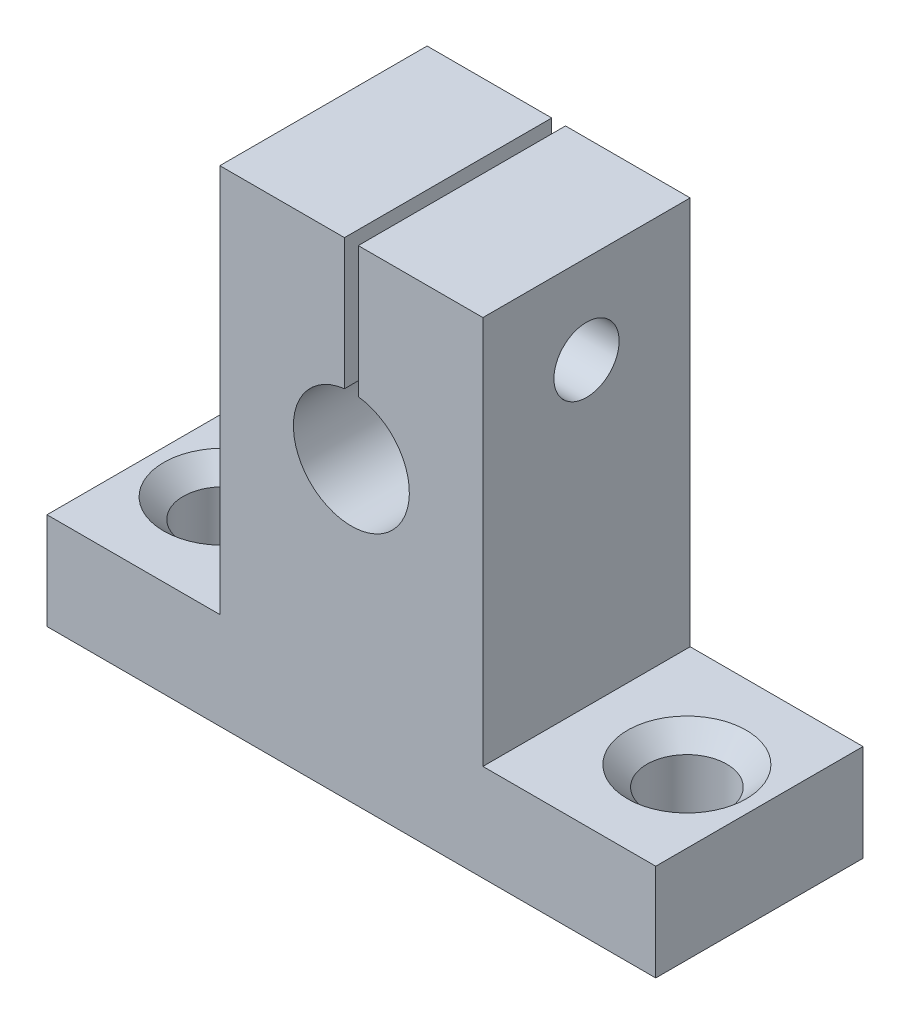
SolidWorks part; units mm, degrees
ref_plane "Front Plane" through (0, 0, 0) normal (0, 0, 1) x (1, 0, 0)
ref_plane "Top Plane" through (0, 0, 0) normal (0, 1, 0) x (1, 0, 0)
ref_plane "Right Plane" through (0, 0, 0) normal (1, 0, 0) x (0, 0, -1)
sketch "Sketch1" plane through (0, 0, 0) normal (0, 0, 1) x (1, 0, 0)
  line L1 (0, 0) -> (42, 0)
  line L2 (0, 0) -> (0, 6.68)
  line L3 (0, 6.68) -> (42, 6.68)
  line L4 (42, 0) -> (42, 6.68)
  line L5 (11.925, 6.68) -> (30.075, 6.68)
  line L6 (11.925, 6.68) -> (11.925, 33.5)
  line L7 (11.925, 33.5) -> (30.075, 33.5)
  line L8 (30.075, 6.68) -> (30.075, 33.5)
  line L9 (20.525, 33.5) -> (21.475, 33.5)
  line L10 (20.525, 33.5) -> (20.525, 20.5)
  line L11 (20.525, 20.5) -> (21.475, 20.5)
  line L12 (21.475, 33.5) -> (21.475, 20.5)
  circle A0 centre (21, 20.5) radius 4
  point P8 (21, 33.5)
  point P9 (21, 6.68)
  point P12 (21, 24.5)
  point P15 (21, 20.5)
  point P20 (21, 20.5)
  dimension "D5" = 8
  dimension "D1" = 18.15
  dimension "D2" = 6.68
  dimension "D3" = 42
  dimension "D4" = 33.5
  dimension "D6" = 0.95
  dimension "D7" = 9
sketch "Sketch2" plane through (0, 0, 0) normal (0, 0, 1) x (1, 0, 0)
  line L0 (11.925, 6.68) -> (0, 6.68)
  line L1 (20.525, 33.5) -> (11.925, 33.5)
  line L4 (11.925, 6.68) -> (30.075, 6.68)
  line L5 (30.075, 6.68) -> (30.075, 33.5)
  line L6 (30.075, 33.5) -> (11.925, 33.5)
  line L7 (11.925, 33.5) -> (11.925, 6.68)
  line L9 (30.075, 6.68) -> (30.075, 33.5)
  line L10 (30.075, 33.5) -> (21.475, 33.5)
  line L11 (11.925, 33.5) -> (11.925, 6.68)
  line L12 (0, 0) -> (42, 0)
  line L13 (42, 0) -> (42, 6.68)
  line L14 (42, 6.68) -> (0, 6.68)
  line L15 (0, 6.68) -> (0, 0)
  line L16 (0, 0) -> (42, 0)
  line L17 (42, 0) -> (42, 6.68)
  line L18 (42, 6.68) -> (30.075, 6.68)
  line L19 (0, 6.68) -> (0, 0)
  line L20 (21.475, 33.5) -> (20.525, 33.5)
  line L21 (20.525, 33.5) -> (20.525, 20.5)
  line L22 (20.525, 20.5) -> (21.475, 20.5)
  line L23 (21.475, 20.5) -> (21.475, 33.5)
  line L25 (20.525, 33.5) -> (20.525, 24.4717)
  line L27 (21.475, 24.4717) -> (21.475, 33.5)
  circle A1 centre (21, 20.5) radius 4
  arc A2 (20.525, 24.4717) -> (21.475, 24.4717) centre (21, 20.5) ccw
  dimension "D1" = 0
  dimension "D2" = 0
  dimension "D3" = 0
  dimension "D4" = 0
extrude "Boss-Extrude1" add sketch "Sketch2" along normal mid plane 14.3
hole_wizard "CBORE for M4 Hex Socket Head Cap Screw1" positions "Sketch3" profile "Sketch5" counterbore size "M4" standard "ISO" end condition through all
sketch "Sketch3" plane through (11.925, 0, 0) normal (-1, 0, 0) x (0, 0, 1)
  line L0 (7.15, 33.5) -> (-7.15, 33.5) construction
  point P0 (0, 27.4)
  point P6 (0, 33.5)
  dimension "D1" = 6.1
sketch "Sketch5" plane through (11.925, 27.4, 0) normal (0, 1, 0) x (0, 0, 1)
  line L0 (0, 0) -> (0, 30.075)
  line L1 (0, 30.075) -> (2.25, 30.075)
  line L3 (2.25, 30.075) -> (2.25, 4.4)
  line L4 (2.25, 4.4) -> (4, 4.4)
  line L5 (4, 4.4) -> (4, 0)
  line L7 (4, 0) -> (0, 0)
  line L11 (0, -6.35) -> (0, 107.95) construction
  dimension "Thru Hole Dia." = 4.5
  dimension "Thru Hole Depth" = 30.075
  dimension "C'Bore Dia." = 8
  dimension "C'Bore Depth" = 4.4
hole_wizard "CSK for M5 Hex Socket Countersunk Cap Screw1" positions "Sketch6" profile "Sketch7" countersink size "M5" standard "ISO" end condition through all
sketch "Sketch6" plane through (0, 6.68, 0) normal (0, 1, 0) x (1, 0, 0)
  line L0 (0, -7.15) -> (0, 7.15) construction
  line L1 (42, -7.15) -> (42, 7.15) construction
  point P0 (5, 0)
  point P2 (37, 0)
  point P11 (0, 0)
  dimension "D1" = 5
  dimension "D2" = 5
sketch "Sketch7" plane through (5, 6.68, 0) normal (1, 0, 0) x (0, 0, 1)
  line L0 (0, 0) -> (0, 6.68)
  line L1 (0, 6.68) -> (2.75, 6.68)
  line L2 (2.75, 6.68) -> (2.75, 1.35)
  line L3 (2.75, 1.35) -> (4.1, 0)
  line L5 (4.1, 0) -> (0, 0)
  line L6 (-2.75, 1.35) -> (-4.1, 0) construction
  line L11 (0, -6.35) -> (0, 107.95) construction
  dimension "Thru Hole Dia." = 5.5
  dimension "Thru Hole Depth" = 6.68
  dimension "Near C'Sink Dia." = 8.2
  dimension "Near C'Sink Angle" = 90
